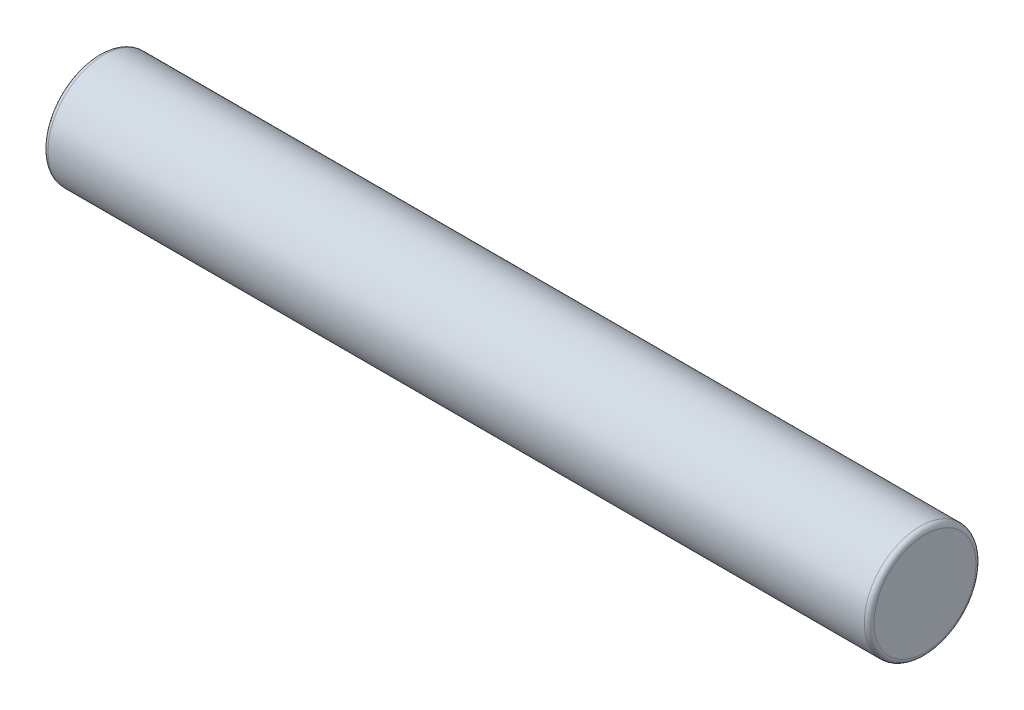
SolidWorks part; units mm, degrees
material "Chrome Stainless Steel"
ref_plane "Front Plane" through (0, 0, 0) normal (0, 0, 1) x (1, 0, 0)
ref_plane "Top Plane" through (0, 0, 0) normal (0, 1, 0) x (1, 0, 0)
ref_plane "Right Plane" through (0, 0, 0) normal (1, 0, 0) x (0, 0, -1)
sketch "Sketch1" plane through (0, 0, 0) normal (1, 0, 0) x (0, 0, -1)
  circle A0 centre (0, 0) radius 1.15
  dimension "D1" = 2.3
extrude "Boss-Extrude1" add sketch "Sketch1" along normal mid plane 17
fillet "Fillet1" radius 0.1 2 edges at (-8.5, 0, -1.15) (8.5, 0, -1.15)
